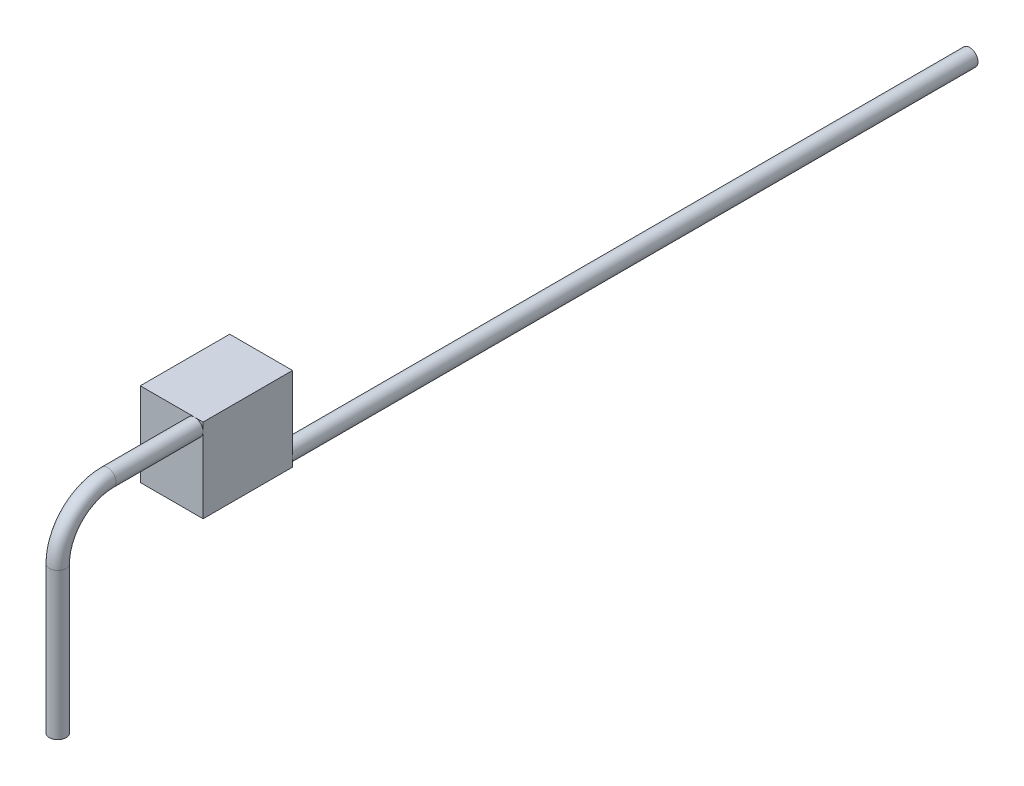
SolidWorks part; units mm, degrees
material "Plain Carbon Steel"
ref_plane "Front Plane" through (0, 0, 0) normal (0, 0, 1) x (1, 0, 0)
ref_plane "Top Plane" through (0, 0, 0) normal (0, 1, 0) x (1, 0, 0)
ref_plane "Right Plane" through (0, 0, 0) normal (1, 0, 0) x (0, 0, -1)
sketch "Sketch1" plane through (0, 0, 0) normal (0, 0, 1) x (1, 0, 0)
  circle A0 centre (0, 0) radius 1.9844
  dimension "D1" = 3.9688
extrude "Boss-Extrude1" add sketch "Sketch1" along normal blind 170
sketch "Sketch2" plane through (0, 0, 170) normal (0, 0, 1) x (1, 0, 0)
  line L1 (-13.0156, -1.9844) -> (1.9844, -1.9844)
  line L2 (-13.0156, -1.9844) -> (-13.0156, 18.0156)
  line L3 (-13.0156, 18.0156) -> (1.9844, 18.0156)
  line L4 (1.9844, -1.9844) -> (1.9844, 18.0156)
  circle A0 centre (0, 0) radius 1.9844 construction
  dimension "D1" = 20
  dimension "D2" = 15
extrude "Boss-Extrude2" add sketch "Sketch2" along normal blind 15 and the other way blind 6.35
sketch "Sketch3" plane through (0, 0, 185) normal (0, 0, 1) x (1, 0, 0)
  line L0 (1.9844, 18.0156) -> (-13.0156, 18.0156) construction
  circle A0 centre (0, 16.0312) radius 1.9844
  dimension "D1" = 3.9688
extrude "Boss-Extrude3" add sketch "Sketch3" along normal blind 20.8
sketch "Sketch4" plane through (0, 0, 205.8) normal (0, 0, 1) x (1, 0, 0)
  circle A0 centre (0, 16.0312) radius 1.9844
sketch "Sketch5" plane through (0, 0, 205.8) normal (0, 0, 1) x (1, 0, 0)
  line L0 (-5.9723, 4.113) -> (7.0862, 4.113) construction
revolve "Revolve5" add sketch "Sketch4" angle 90 about L0
sketch "Sketch6" plane through (0, 4.113, 0) normal (0, -1, 0) x (1, 0, 0)
  circle A0 centre (0, 217.7183) radius 1.9844
  circle A1 centre (0, 217.7183) radius 1.9844 construction
extrude "Boss-Extrude4" add sketch "Sketch6" along normal blind 35
